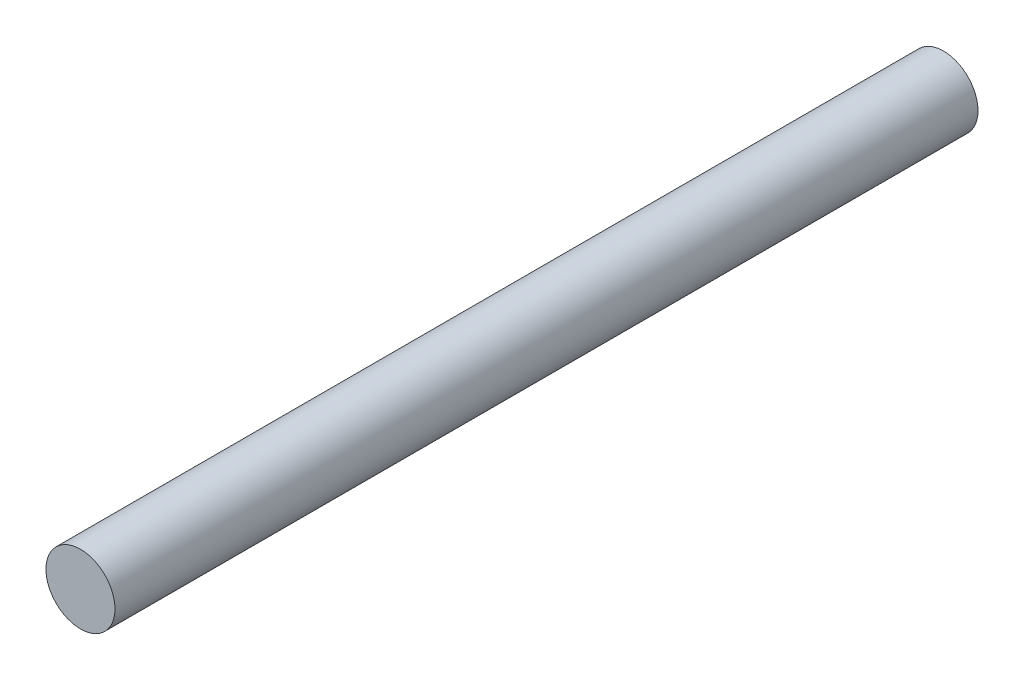
SolidWorks part; units mm, degrees
ref_plane "정면" through (0, 0, 0) normal (0, 0, 1) x (1, 0, 0)
ref_plane "윗면" through (0, 0, 0) normal (0, 1, 0) x (1, 0, 0)
ref_plane "우측면" through (0, 0, 0) normal (1, 0, 0) x (0, 0, -1)
sketch "스케치1" plane through (0, 0, 0) normal (0, 0, 1) x (1, 0, 0)
  circle A0 centre (0, 0) radius 4
  dimension "D1" = 8
extrude "보스-돌출1" add sketch "스케치1" along normal blind 100
